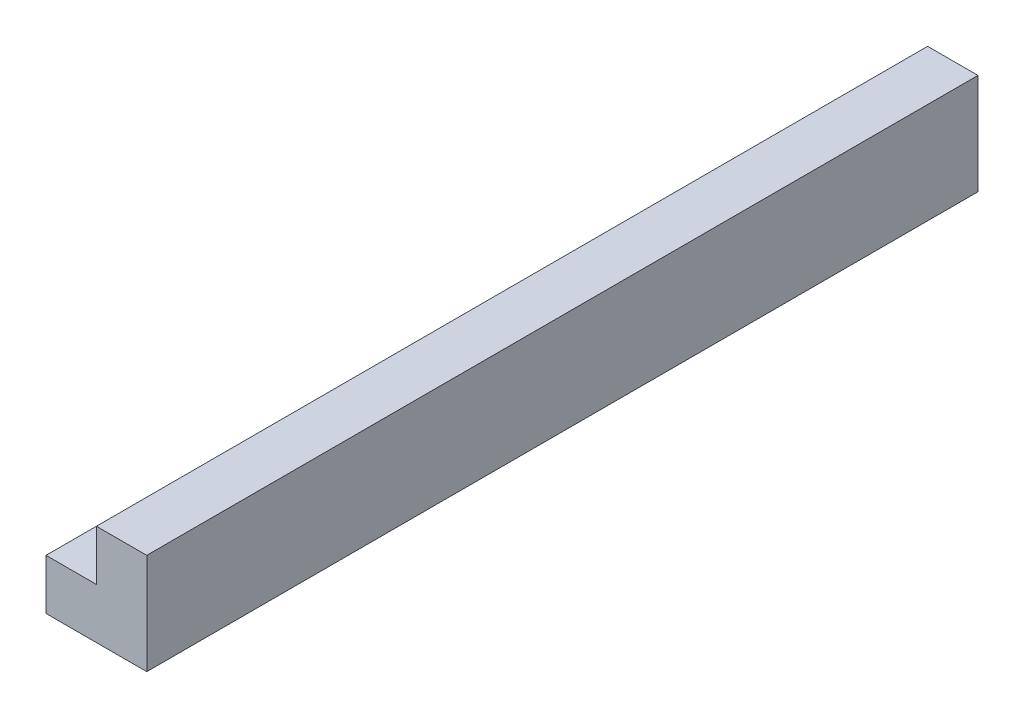
SolidWorks part; units mm, degrees
ref_plane "Plan de face" through (0, 0, 0) normal (0, 0, 1) x (1, 0, 0)
ref_plane "Plan de dessus" through (0, 0, 0) normal (0, 1, 0) x (1, 0, 0)
ref_plane "Plan de droite" through (0, 0, 0) normal (1, 0, 0) x (0, 0, -1)
sketch "Esquisse1" plane through (0, 0, 0) normal (0, 0, 1) x (1, 0, 0)
  line L0 (0, 0) -> (20, 0)
  line L1 (0, 0) -> (20, 0) construction
  line L2 (0, 0) -> (0, 20) construction
  line L3 (0, 20) -> (20, 20) construction
  line L4 (20, 0) -> (20, 20) construction
  line L5 (20, 0) -> (20, 20)
  line L6 (20, 20) -> (10, 20)
  line L7 (10, 20) -> (10, 10)
  line L8 (10, 10) -> (0, 10)
  line L9 (0, 10) -> (0, 0)
  dimension "D1" = 20
  dimension "D2" = 20
extrude "Boss.-Extru.1" add sketch "Esquisse1" along normal blind 165
equation "\"Largeur\"= 20"
equation "\"Longueur\"= 165"
equation "\"Hauteur\"= 20"
equation "\"D1@Esquisse1\"=\"Largeur\""
equation "\"D2@Esquisse1\"=\"Hauteur\""
equation "\"D1@Boss.-Extru.1\"=\"Longueur\""
